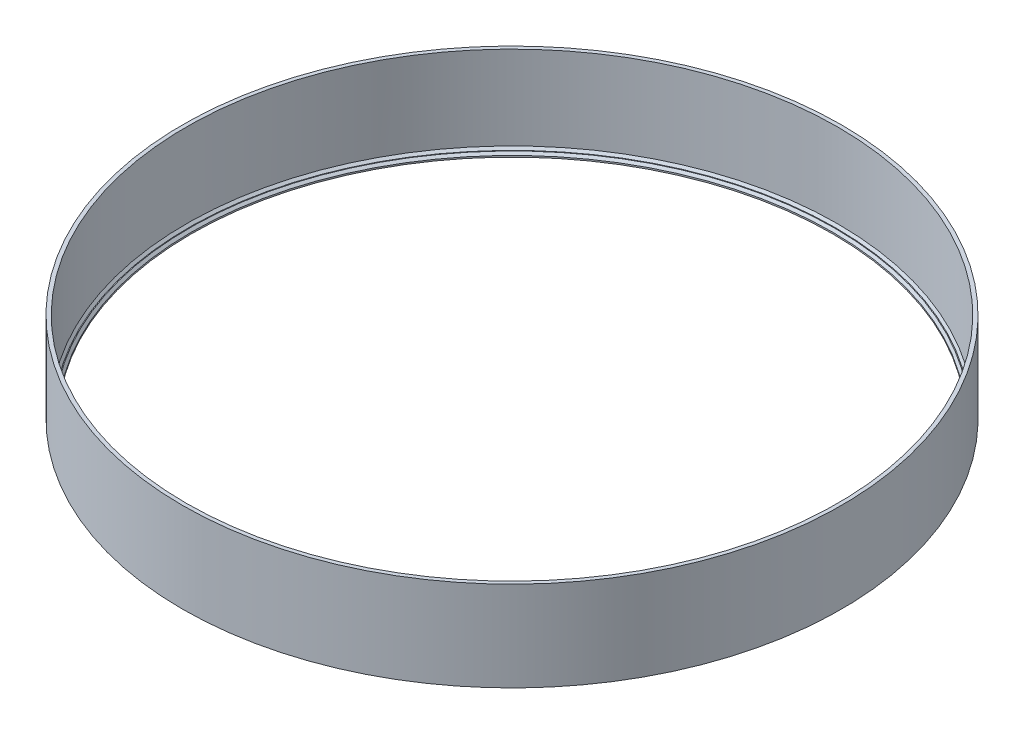
SolidWorks part; units mm, degrees
ref_plane "Alzado" through (0, 0, 0) normal (0, 0, 1) x (1, 0, 0)
ref_plane "Planta" through (0, 0, 0) normal (0, 1, 0) x (1, 0, 0)
ref_plane "Vista lateral" through (0, 0, 0) normal (1, 0, 0) x (0, 0, -1)
sketch "Croquis1" plane through (0, 0, 0) normal (0, 1, 0) x (1, 0, 0)
  circle A0 centre (0, 0) radius 44
  circle A1 centre (0, 0) radius 43.5
  dimension "D1" = 88
  dimension "D2" = 0.5
extrude "Saliente-Extruir1" add sketch "Croquis1" along normal blind 12
sketch "Croquis2" plane through (0, 0, 0) normal (0, -1, 0) x (1, 0, 0)
  circle A0 centre (0, 0) radius 44
  circle A1 centre (0, 0) radius 42.8
  circle A2 centre (0, 0) radius 44 construction
  dimension "D1" = 1.2
extrude "Saliente-Extruir2" add sketch "Croquis2" against normal blind 0.5
chamfer "Chaflán1" distance 0.3 angle 45 2 edges at (0, 0.5, -42.8) (0, 0.5, -43.5)
